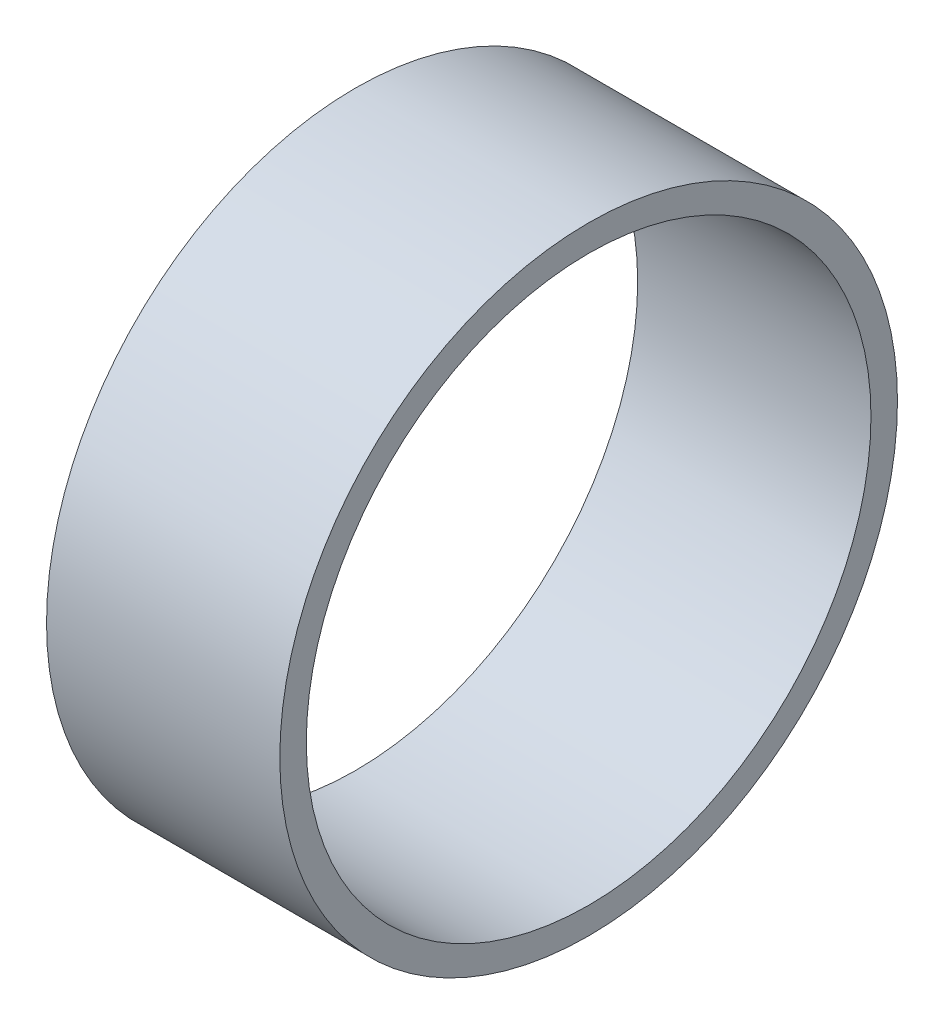
SolidWorks part; units mm, degrees
material "6061 Alloy"
ref_plane "Front Plane" through (0, 0, 0) normal (0, 0, 1) x (1, 0, 0)
ref_plane "Top Plane" through (0, 0, 0) normal (0, 1, 0) x (1, 0, 0)
ref_plane "Right Plane" through (0, 0, 0) normal (1, 0, 0) x (0, 0, -1)
sketch "Sketch1" plane through (0, 0, 0) normal (1, 0, 0) x (0, 0.0422, -0.9991)
  circle A0 centre (28.5429, 18.9571) radius 10.65
  circle A1 centre (28.5429, 18.9571) radius 11.65
  dimension "D1" = 1
extrude "Boss-Extrude1" add sketch "Sketch1" along normal blind 8.8
